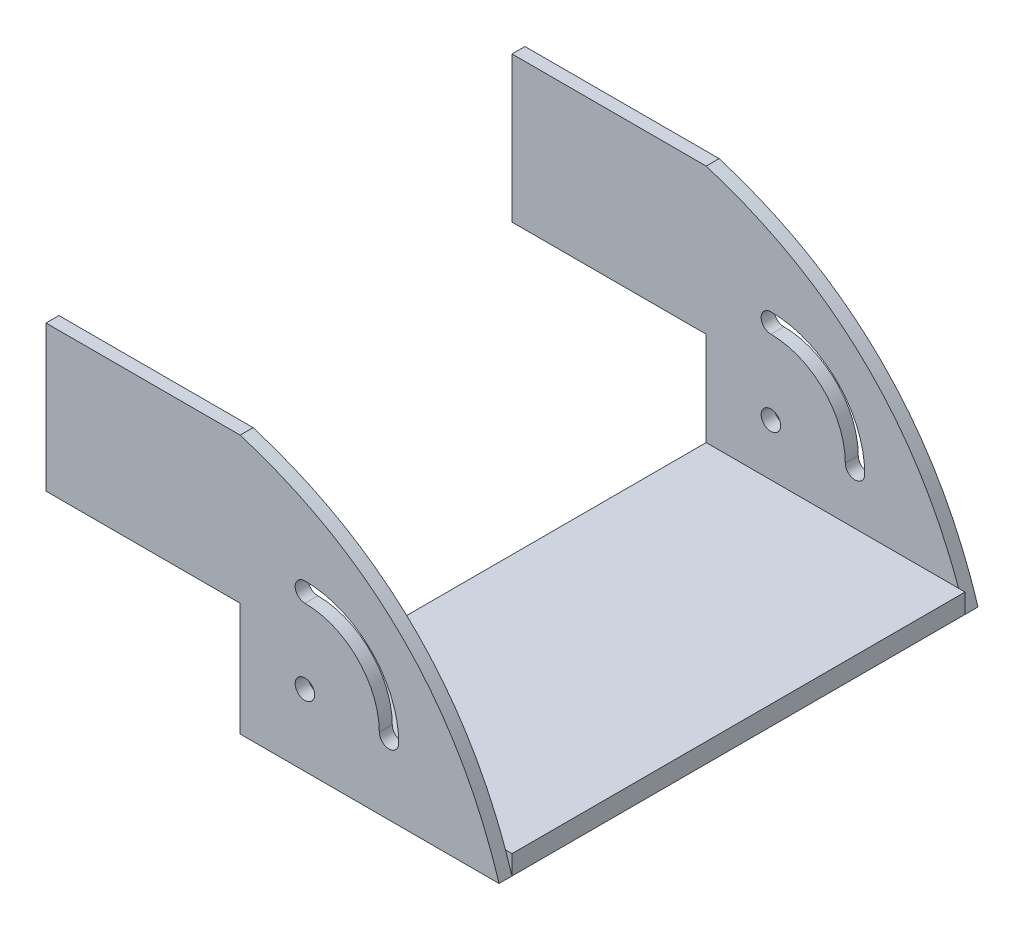
SolidWorks part; units mm, degrees
ref_plane "Plan de face" through (0, 0, 0) normal (0, 0, 1) x (1, 0, 0)
ref_plane "Plan de dessus" through (0, 0, 0) normal (0, 1, 0) x (1, 0, 0)
ref_plane "Plan de droite" through (0, 0, 0) normal (1, 0, 0) x (0, 0, -1)
sketch "Esquisse1" plane through (0, 0, 0) normal (0, 0, 1) x (1, 0, 0)
  line L0 (-29.0568, -6.2568) -> (-29.0568, -9.2568)
  line L1 (-29.0568, -9.2568) -> (10.9432, -9.2568)
  line L2 (10.9432, -9.2568) -> (10.9432, -6.2568)
  line L3 (10.9432, -6.2568) -> (-29.0568, -6.2568)
  dimension "D1" = 3
  dimension "D2" = 40
  dimension "D3" = 3
extrude "Boss.-Extru.2" add sketch "Esquisse1" along normal blind 70
sketch "Esquisse3" plane through (0, 0, 70) normal (0, 0, 1) x (1, 0, 0)
  line L0 (-29.0568, -9.2568) -> (-1.8859, 15.3866) construction
  line L1 (-29.0568, -9.2568) -> (10.9432, -9.2568)
  line L2 (-29.0568, -9.2568) -> (-29.0568, 8.2432)
  line L3 (10.9432, -6.2568) -> (-29.0568, -6.2568) construction
  line L4 (-29.0568, 30.7432) -> (-59.0568, 30.7432)
  line L7 (-29.0568, 8.2432) -> (-59.0568, 8.2432)
  line L8 (-59.0568, 30.7432) -> (-59.0568, 8.2432)
  circle A0 centre (-19.0568, 1.7432) radius 1.5
  arc A1 (-4.5568, 1.7432) -> (-19.0568, 16.2432) centre (-19.0568, 1.7432) ccw
  arc A2 (-7.5568, 1.7432) -> (-19.0568, 13.2432) centre (-19.0568, 1.7432) ccw
  arc A3 (-19.0568, 16.2432) -> (-19.0568, 13.2432) centre (-19.0568, 14.7432) ccw
  arc A4 (-7.5568, 1.7432) -> (-4.5568, 1.7432) centre (-6.0568, 1.7432) ccw
  spline S0 degree 2 poles (-29.0568, 30.7432) (1.3592, 21.3531) (10.9432, -9.2568) knots 0 0 0 1 1 1
  dimension "D1" = 3
  dimension "D2" = 1.5
  dimension "D3" = 1.5
  dimension "D4" = 40
  dimension "D5" = 6.5
  dimension "D6" = 10
  dimension "D7" = 40
  dimension "D8" = 10
  dimension "D9" = 30
  dimension "D10" = 8
extrude "Boss.-Extru.3" add sketch "Esquisse3" along normal blind 2
pattern_linear "Répétition linéaire1" count 2 spacing 72 along (0, 0, -1) of "Boss.-Extru.3"
